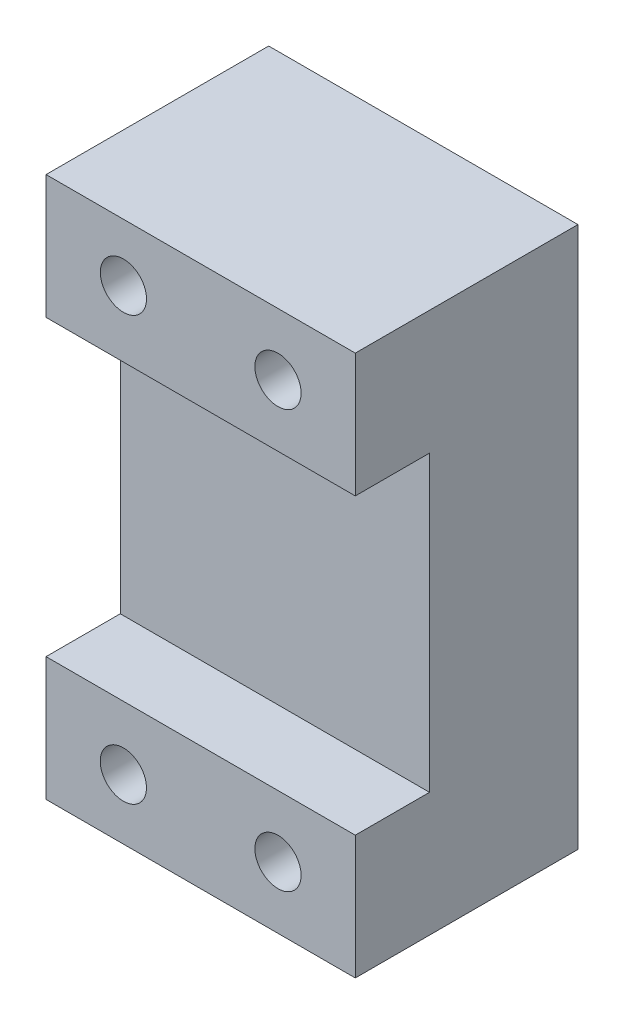
SolidWorks part; units mm, degrees
ref_plane "Front Plane" through (0, 0, 0) normal (0, 0, 1) x (1, 0, 0)
ref_plane "Top Plane" through (0, 0, 0) normal (0, 1, 0) x (1, 0, 0)
ref_plane "Right Plane" through (0, 0, 0) normal (1, 0, 0) x (0, 0, -1)
sketch "Sketch1" plane through (0, 0, 0) normal (0, 0, 1) x (1, 0, 0)
  line L1 (0, 0) -> (25.4, 0)
  line L2 (0, 0) -> (0, 44.45)
  line L3 (0, 44.45) -> (25.4, 44.45)
  line L4 (25.4, 0) -> (25.4, 44.45)
  dimension "D1" = 25.4
  dimension "D2" = 44.45
extrude "Boss-Extrude2" add sketch "Sketch1" along normal blind 18.288
sketch "Sketch3" plane through (0, 0, 18.288) normal (0, 0, 1) x (1, 0, 0)
  line L0 (0, 44.45) -> (0, 0) construction
  line L1 (0, 34.29) -> (25.4, 34.29)
  line L2 (0, 34.29) -> (0, 10.16)
  line L3 (0, 10.16) -> (25.4, 10.16)
  line L4 (25.4, 34.29) -> (25.4, 10.16)
  line L5 (25.4, 0) -> (25.4, 44.45) construction
  dimension "D1" = 24.13
  dimension "D2" = 10.16
extrude "Cut-Extrude1" cut sketch "Sketch3" against normal blind 6.096
hole_wizard "CBORE for #6 Binding Head Machine Screw1" positions "3DSketch2" profile "Sketch5" counterbore size "#6" standard "ANSI Inch" end condition through all
sketch3d "3DSketch2"
  line L0 (25.4, 44.45, 0) -> (0, 44.45, 0) construction
  line L1 (25.4, 0, 0) -> (25.4, 44.45, 0) construction
  line L2 (0, 0, 0) -> (25.4, 0, 0) construction
  point P0 (19.05, 5.08, 0)
  point P2 (6.3507, 4.9483, 0)
  point P4 (19.05, 39.37, 0)
  point P6 (6.355, 39.7269, 0)
  point P7 (0, 0, 0)
  point P12 (0, 0, 0)
  dimension "D1" = 12.7
  dimension "D2" = 5.08
  dimension "D3" = 6.35
  dimension "D4" = 12.7
  dimension "D5" = 6.35
  dimension "D6" = 5.08
sketch "Sketch5" plane through (19.05, 5.08, 0) normal (1, 0, 0) x (0, 1, 0)
  line L0 (0, 0) -> (0, 18.288)
  line L1 (0, 18.288) -> (1.8986, 18.288)
  line L3 (1.8986, 18.288) -> (1.8986, 2.2098)
  line L4 (1.8986, 2.2098) -> (3.9687, 2.2098)
  line L5 (3.9687, 2.2098) -> (3.9687, 0)
  line L7 (3.9687, 0) -> (0, 0)
  line L11 (0, -6.35) -> (0, 107.95) construction
  dimension "Thru Hole Dia." = 3.7973
  dimension "Thru Hole Depth" = 18.288
  dimension "C'Bore Dia." = 7.9375
  dimension "C'Bore Depth" = 2.2098
